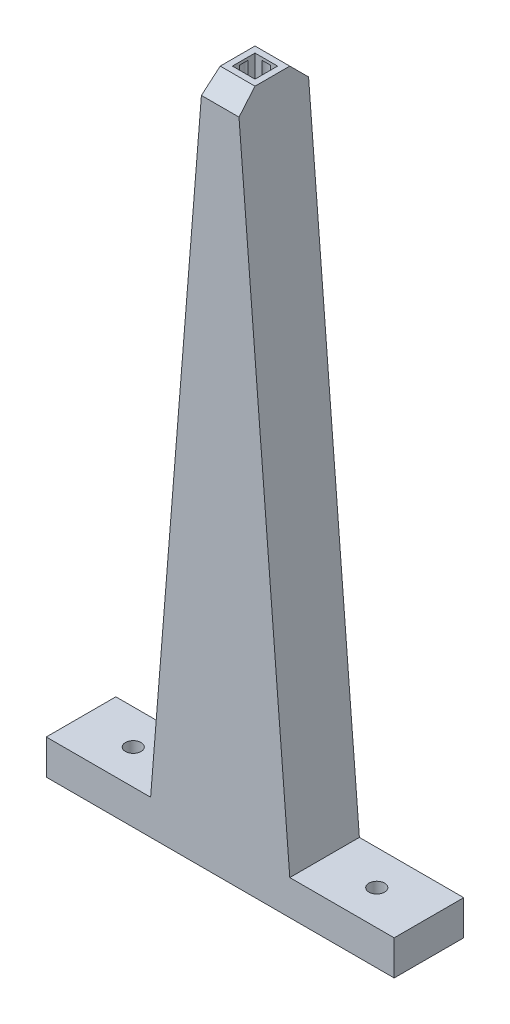
SolidWorks part; units mm, degrees
ref_plane "Plano frontal" through (0, 0, 0) normal (0, 0, 1) x (1, 0, 0)
ref_plane "Plano superior" through (0, 0, 0) normal (0, 1, 0) x (1, 0, 0)
ref_plane "Plano direito" through (0, 0, 0) normal (1, 0, 0) x (0, 0, -1)
sketch "Esboço7" plane through (0, 0, 0) normal (0, 0, 1) x (1, 0, 0)
  line L0 (0, 0) -> (100, 0)
  line L1 (100, 0) -> (100, 10)
  line L2 (100, 10) -> (70, 10)
  line L3 (70, 10) -> (55, 197)
  line L4 (55, 197) -> (45, 197)
  line L5 (45, 197) -> (30, 10)
  line L6 (30, 10) -> (0, 10)
  line L7 (0, 10) -> (0, 0)
  dimension "D1" = 10
  dimension "D2" = 10
  dimension "D3" = 100
  dimension "D4" = 187
  dimension "D6" = 30
extrude "Ressalto-extrusão4" add sketch "Esboço7" along normal blind 20
sketch "Esboço8" plane through (0, 197, 0) normal (0, 1, 0) x (1, 0, 0)
  line L0 (45, -10) -> (55, -10) construction
  line L1 (46.75, -6.75) -> (53.25, -6.75)
  line L2 (46.75, -6.75) -> (46.75, -13.25)
  line L3 (46.75, -13.25) -> (53.25, -13.25)
  line L4 (53.25, -6.75) -> (53.25, -13.25)
  line L5 (45, -20) -> (45, 0) construction
  line L6 (55, -20) -> (55, 0) construction
  line L7 (50, 0) -> (50, -20) construction
  line L8 (55, 0) -> (45, 0) construction
  line L9 (55, -20) -> (45, -20) construction
  dimension "D1" = 6.5
  dimension "D2" = 6.5
  dimension "D3" = 3.25
  dimension "D4" = 3.25
extrude "Corte-extrusão1" cut sketch "Esboço8" against normal blind 15
sketch "Esboço9" plane through (0, 197, 0) normal (0, 1, 0) x (1, 0, 0)
  line L0 (50, -6.75) -> (50, -13.25) construction
  line L1 (53.25, -6.75) -> (46.75, -6.75) construction
  line L2 (46.75, -13.25) -> (53.25, -13.25) construction
  line L3 (46.75, -10) -> (53.25, -10) construction
  line L4 (46.75, -6.75) -> (46.75, -13.25) construction
  line L5 (53.25, -13.25) -> (53.25, -6.75) construction
  line L6 (46.75, -6.75) -> (53.25, -6.75) construction
  line L7 (48.75, -6.75) -> (51.25, -6.75)
  line L8 (53.25, -8.75) -> (53.25, -11.25)
  line L9 (46.75, -8.75) -> (46.75, -11.25)
  line L10 (48.75, -13.25) -> (51.25, -13.25)
  line L11 (46.75, -6.75) -> (46.75, -13.25) construction
  arc A0 (51.25, -6.75) -> (48.75, -6.75) centre (50, -7.5792) ccw
  arc A1 (53.25, -11.25) -> (53.25, -8.75) centre (52.4208, -10) ccw
  arc A2 (48.75, -13.25) -> (51.25, -13.25) centre (50, -12.4208) ccw
  arc A3 (46.75, -8.75) -> (46.75, -11.25) centre (47.5792, -10) ccw
  point P31 (50, -10)
  dimension "D1" = 3
  dimension "D2" = 2
  dimension "D3" = 4
extrude "Corte-extrusão2" cut sketch "Esboço9" against normal blind 4 from offset 1 offset against normal yes
chamfer "Chanfro1" distance 0.2 angle 45 4 edges at (46.75, 196, 10) (50, 196, 6.75) (53.25, 196, 10) (50, 196, 13.25)
chamfer "Chanfro2" distance 5 angle 45 2 edges at (50, 197, 0) (50, 197, 20)
sketch "Esboço10" plane through (0, 10, 0) normal (0, 1, 0) x (1, 0, 0)
  line L0 (0, -10) -> (100, -10) construction
  line L1 (0, -20) -> (0, 0) construction
  line L2 (100, -20) -> (100, 0) construction
  circle A0 centre (15, -10) radius 2.25
  circle A1 centre (85, -10) radius 2.25
  dimension "D1" = 4.5
  dimension "D2" = 4.5
  dimension "D3" = 15
  dimension "D4" = 15
extrude "Corte-extrusão3" cut sketch "Esboço10" against normal through all
